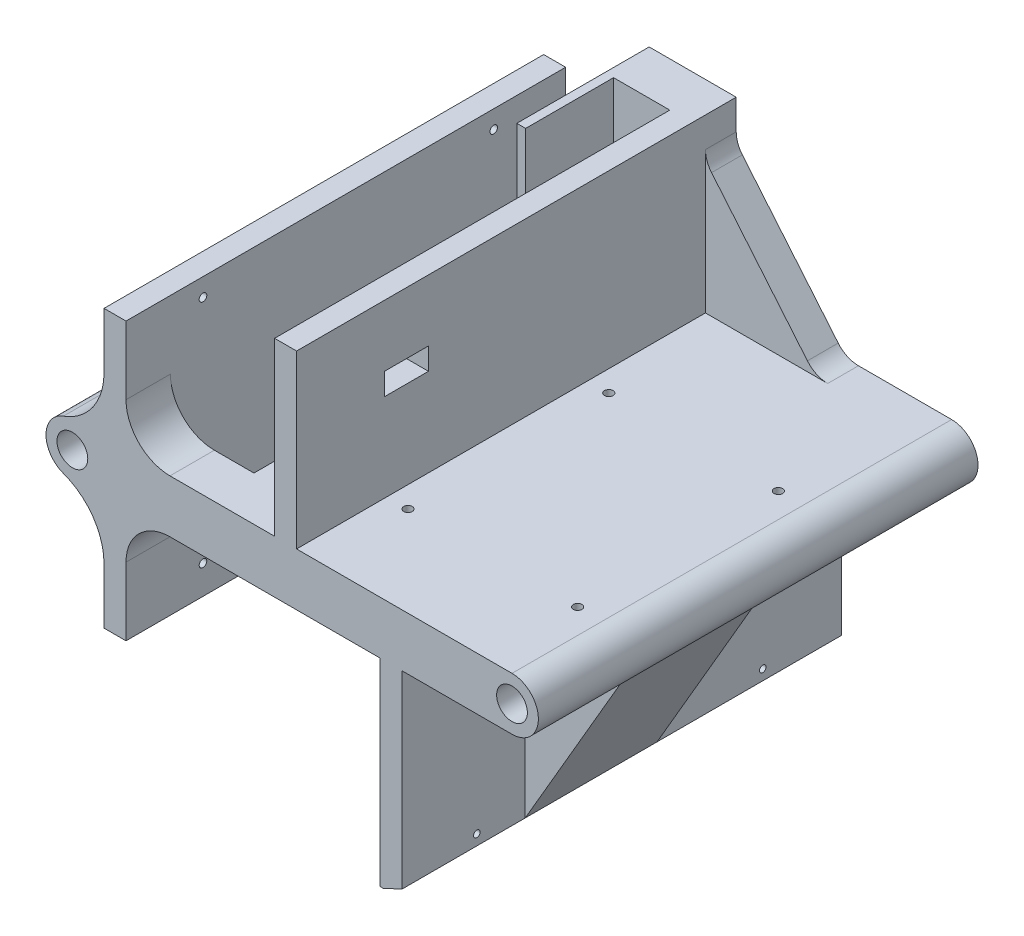
SolidWorks part; units mm, degrees
ref_plane "Front Plane" through (0, 0, 0) normal (0, 0, 1) x (1, 0, 0)
ref_plane "Top Plane" through (0, 0, 0) normal (0, 1, 0) x (1, 0, 0)
ref_plane "Right Plane" through (0, 0, 0) normal (1, 0, 0) x (0, 0, -1)
sketch "Sketch1" plane through (0, 0, 0) normal (0, 0, 1) x (1, 0, 0)
  line L0 (0, 7.62) -> (127, 7.62)
  line L1 (0, -7.62) -> (127, -7.62)
  circle A0 centre (0, 0) radius 4.445
  arc A1 (0, 7.62) -> (0, -7.62) centre (0, 0) ccw
  arc A2 (127, -7.62) -> (127, 7.62) centre (127, 0) ccw
  circle A3 centre (127, 0) radius 4.445
  dimension "D1" = 15.24
  dimension "D2" = 8.89
  dimension "D3" = 2
extrude "Boss-Extrude1" add sketch "Sketch1" along normal blind 127 contours L1 A2 L0 A1 A3 A0
sketch "Sketch7" plane through (0, 0, 127) normal (0, 0, 1) x (1, 0, 0)
  line L0 (64.77, 64.77) -> (58.42, 64.77)
  line L1 (9.144, -40.005) -> (15.494, -40.005)
  line L2 (9.144, -40.005) -> (9.144, 40.005)
  line L3 (9.144, 40.005) -> (15.494, 40.005)
  line L4 (15.494, -40.005) -> (15.494, 40.005)
  line L5 (64.77, -1.27) -> (58.42, -1.27)
  line L6 (64.77, -1.27) -> (64.77, 64.77)
  line L8 (58.42, -1.27) -> (58.42, 64.77)
  line L9 (0, 7.62) -> (127, 7.62) construction
  line L10 (0, -7.62) -> (127, -7.62) construction
  line L11 (88.9, -7.62) -> (95.25, -7.62)
  line L12 (88.9, -7.62) -> (88.9, -64.77)
  line L13 (88.9, -64.77) -> (95.25, -64.77)
  line L14 (95.25, -7.62) -> (95.25, -64.77)
  circle A0 centre (127, 0) radius 4.445 construction
  line M7 (0, -7.62) -> (127, -7.62)
  dimension "D4" = 62.23
  dimension "D1" = 6.35
  dimension "D2" = 6.35
  dimension "D3" = 9.144
  dimension "D5" = 80.01
  dimension "D6" = 66.04
  dimension "D7" = 57.15
  dimension "D8" = 32.385
  dimension "D9" = 6.35
  dimension "D10" = 57.15
  dimension "D11" = 24.13
extrude "Boss-Extrude4" add sketch "Sketch7" against normal blind 127 contours L14 L12 L13 M7 | L2 L3 L4 L1 | L6 L0 L8 L5
sketch "Sketch8" plane through (9.144, 0, 0) normal (-1, 0, 0) x (0, 0, 1)
  line L0 (127, 7.62) -> (127, 40.005) construction
  circle A0 centre (104.7632, 34.8014) radius 1.1
  circle A1 centre (104.7632, -31.6986) radius 1.1
  circle A2 centre (20.7632, -31.6986) radius 1.1
  circle A3 centre (20.7632, 34.8014) radius 1.1
  dimension "D1" = 2.2
  dimension "D2" = 2.2
  dimension "D3" = 2.2
  dimension "D4" = 2.2
  dimension "D5" = 66.5
  dimension "D6" = 84
  dimension "D7" = 22.2368
sketch "Sketch9" plane through (0, 0, 127) normal (0, 0, 1) x (1, 0, 0)
  line L0 (-7.62, 0) -> (134.62, 0) construction
  arc A0 (0, 7.62) -> (0, -7.62) centre (0, 0) ccw construction
  arc A1 (127, -7.62) -> (127, 7.62) centre (127, 0) ccw construction
  circle A2 centre (63.5, 0) radius 69.85 construction
  dimension "D1" = 139.7
extrude "Cut-Extrude2" cut sketch "Sketch8" against normal up to next
sketch "Sketch10" [suppressed] plane through (64.77, 0, 0) normal (1, 0, 0) x (0, 0, -1)
  line L0 (-66.7, -10.9316) -> (-66.7, -52.605) construction
  line L1 (-108, -35.54) -> (32.6497, -35.54) construction
  line L2 (0, -64.77) -> (-127, -64.77) construction
  line L3 (0, 7.62) -> (0, 64.77) construction
  circle A5 centre (-108, -59.69) radius 0.9
  circle A6 centre (-108, -11.39) radius 0.9
  circle A7 centre (-25.4, -11.39) radius 0.9
  circle A8 centre (-25.4, -59.69) radius 0.9
  dimension "D4" = 5.08
  dimension "D3" = 1.8
  dimension "D1" = 24.15
  dimension "D2" = 41.3
  dimension "D5" = 25.4
sketch "Sketch11" plane through (0, -7.62, 0) normal (0, -1, 0) x (1, 0, 0)
  line L0 (15.494, 127) -> (15.494, 0) construction
  line L1 (15.494, 114.1726) -> (58.42, 114.1726)
  line L2 (15.494, 114.1726) -> (15.494, 12.8274)
  line L3 (15.494, 12.8274) -> (58.42, 12.8274)
  line L4 (58.42, 114.1726) -> (58.42, 12.8274)
  line L10 (58.42, 127) -> (58.42, 0) construction
  line L11 (-7.62, 63.5) -> (134.62, 63.5) construction
  line L12 (-7.62, 127) -> (-7.62, 0) construction
  line L13 (134.62, 0) -> (134.62, 127) construction
  point P14 (58.42, 63.5)
extrude "Cut-Extrude4" cut sketch "Sketch11" against normal up to next
fillet "Fillet1" radius 17.78 2 edges at (9.144, -7.62, 63.5) (9.144, 7.62, 63.5)
ref_plane "Plane1" through (0, 0, 50.8) normal (0, 0, 1) x (1, 0, 0)
sketch "Sketch14" plane through (0, 7.62, 0) normal (0, 1, 0) x (1, 0, 0)
  line L1 (64.77, 0) -> (64.77, -127) construction
  circle A0 centre (119.866, -42.9066) radius 1.25
  circle A1 centre (70.866, -42.9066) radius 1.25
  circle A2 centre (70.866, -100.9066) radius 1.25
  circle A3 centre (119.866, -100.9066) radius 1.25
  dimension "D3" = 6.096
  dimension "D4" = 2.5
  dimension "D1" = 58
  dimension "D2" = 49
extrude "Cut-Extrude6" cut sketch "Sketch14" against normal up to next
sketch "Sketch15" plane through (0, 64.77, 0) normal (0, 1, 0) x (1, 0, 0)
  line L1 (58.42, 0) -> (64.77, 0)
  line L2 (58.42, 0) -> (58.42, -127)
  line L3 (58.42, -127) -> (64.77, -127)
  line L4 (64.77, 0) -> (64.77, -127)
extrude "Cut-Extrude7" cut sketch "Sketch15" against normal blind 7.62
sketch "Sketch16" plane through (58.42, 0, 0) normal (-1, 0, 0) x (0, 0, 1)
  line L0 (12.8274, 7.62) -> (12.8274, -7.62) construction
  line L1 (0, 7.62) -> (12.8274, 7.62)
  line L2 (0, 7.62) -> (0, 57.15)
  line L3 (0, 57.15) -> (12.8274, 57.15)
  line L4 (12.8274, 7.62) -> (12.8274, 57.15)
  line L5 (0, 57.15) -> (127, 57.15) construction
extrude "Boss-Extrude5" add sketch "Sketch16" along normal blind 16.256
sketch "Sketch17" plane through (42.164, 0, 0) normal (-1, 0, 0) x (0, 0, 1)
  line L1 (0, 57.15) -> (38.2274, 57.15)
  line L2 (0, 57.15) -> (0, 7.62)
  line L3 (0, 7.62) -> (38.2274, 7.62)
  line L4 (38.2274, 57.15) -> (38.2274, 7.62)
  line L5 (0, 7.62) -> (12.8274, 7.62) construction
  line L6 (12.8274, 7.62) -> (12.8274, 57.15) construction
  line L7 (12.8274, 7.62) -> (12.8274, 57.15) construction
  dimension "D1" = 25.4
extrude "Boss-Extrude6" add sketch "Sketch17" along normal blind 2.54
sketch "Sketch18" plane through (0, 0, 12.8274) normal (0, 0, 1) x (1, 0, 0)
  line L1 (39.624, 7.62) -> (61.2561, 7.62)
  line L2 (39.624, 7.62) -> (39.624, -7.62)
  line L3 (39.624, -7.62) -> (61.2561, -7.62)
  line L4 (61.2561, 7.62) -> (61.2561, -7.62)
  line L6 (39.624, 7.62) -> (39.624, 57.15) construction
  line L7 (15.494, 7.62) -> (58.42, 7.62) construction
  line L8 (15.494, -7.62) -> (88.9, -7.62) construction
extrude "Boss-Extrude7" add sketch "Sketch18" along normal up to surface (101.3453 mm away) up to face at (36.957, 0, 114.1726)
fillet "Fillet2" radius 12.7 3 edges at (15.494, 7.62, 6.4137) (15.494, -7.62, 120.5863) (15.494, 7.62, 120.5863)
sketch "Sketch23" plane through (95.25, 0, 0) normal (1, 0, 0) x (0, 0, -1)
  line L0 (-64.11, -18.3537) -> (-64.11, -38.8153) construction
  line L1 (-92.2214, -35.072) -> (-30.461, -35.072) construction
  line L2 (0, -7.62) -> (-127, -7.62) construction
  line L3 (-127, 69.85) -> (-127, -69.85) construction
  circle A0 centre (-105.41, -10.922) radius 0.95
  circle A1 centre (-22.81, -10.922) radius 0.95
  circle A2 centre (-22.81, -59.222) radius 0.95
  circle A3 centre (-105.41, -59.222) radius 0.95
  dimension "D1" = 1.9
  dimension "D2" = 24.15
  dimension "D3" = 41.3
  dimension "D4" = 3.302
  dimension "D5" = 21.59
extrude "Cut-Extrude8" cut sketch "Sketch23" against normal blind 25.4
chamfer "Chamfer1" distance 2.54 angle 65 1 edges at (95.25, -64.77, 63.5)
ref_plane "Plane2" through (0, 0, 91.44) normal (0, 0, 1) x (1, 0, 0)
sketch "Sketch25" plane through (0, 0, 91.44) normal (0, 0, 1) x (1, 0, 0)
  line L4 (127, -7.62) -> (95.25, -7.62)
  line L5 (95.25, -7.62) -> (95.25, -62.23)
  line L6 (95.25, -62.23) -> (127, -7.62)
extrude "Boss-Extrude10" add sketch "Sketch25" against normal blind 38.1
sketch "Sketch26" plane through (0, 0, 0) normal (0, 0, -1) x (-1, 0, 0)
  line L1 (-88.9, -7.62) -> (-15.494, -7.62)
  line L2 (-88.9, -7.62) -> (-88.9, -40.005)
  line L3 (-88.9, -40.005) -> (-15.494, -40.005)
  line L4 (-15.494, -7.62) -> (-15.494, -40.005)
  line L5 (-15.494, -40.005) -> (-15.494, -7.62) construction
  dimension "D2" = 73.406
extrude "Boss-Extrude11" add sketch "Sketch26" against normal up to surface (12.8274 mm away) up to face at (27.1599, 3.5379, 12.8274)
fillet "Fillet3" radius 12.7 1 edges at (88.9, -40.005, 6.4137)
sketch "Sketch27" plane through (0, 0, 0) normal (0, 0, -1) x (-1, 0, 0)
  line L0 (-64.77, 7.62) -> (-64.77, 45.72)
  line L2 (-64.77, 45.72) -> (-96.52, 7.62)
  line L3 (-64.77, 7.62) -> (-127, 7.62) construction
  line L4 (-96.52, 7.62) -> (-64.77, 7.62)
  dimension "D1" = 38.1
  dimension "D2" = 31.75
extrude "Boss-Extrude12" add sketch "Sketch27" against normal blind 8.89
fillet "Fillet4" radius 7.62 2 edges at (96.52, 7.62, 4.445) (64.77, 45.72, 4.445)
sketch "Sketch28" plane through (0, -7.62, 0) normal (0, -1, 0) x (1, 0, 0)
  line L0 (28.194, 127) -> (58.42, 127) construction
  line L1 (49.5062, 101.6) -> (55.8562, 101.6)
  line L2 (49.5062, 101.6) -> (49.5062, 88.9)
  line L3 (49.5062, 88.9) -> (55.8562, 88.9)
  line L4 (55.8562, 101.6) -> (55.8562, 88.9)
  dimension "D1" = 12.7
  dimension "D2" = 6.35
  dimension "D3" = 25.4
extrude "Cut-Extrude9" cut sketch "Sketch28" against normal blind 25.4
sketch "Sketch29" plane through (64.77, 0, 0) normal (1, 0, 0) x (0, 0, -1)
  line L0 (-127, 69.85) -> (-127, -69.85) construction
  line L1 (-101.6, 39.37) -> (-88.9, 39.37)
  line L2 (-101.6, 39.37) -> (-101.6, 33.02)
  line L3 (-101.6, 33.02) -> (-88.9, 33.02)
  line L4 (-88.9, 39.37) -> (-88.9, 33.02)
  line L5 (-127, 7.62) -> (-8.89, 7.62) construction
  dimension "D1" = 6.35
  dimension "D2" = 12.7
  dimension "D3" = 25.4
  dimension "D4" = 25.4
extrude "Cut-Extrude10" cut sketch "Sketch29" against normal blind 25.4
